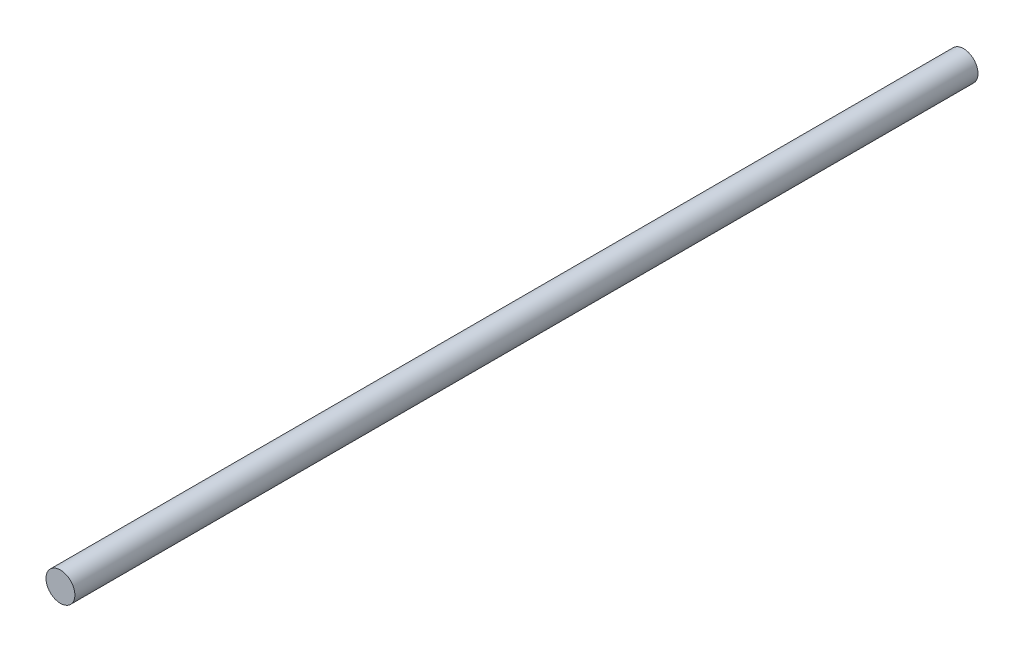
SolidWorks part; units mm, degrees
material "1.4000 (X6Cr13)"
ref_plane "Plan de face" through (0, 0, 0) normal (0, 0, 1) x (1, 0, 0)
ref_plane "Plan de dessus" through (0, 0, 0) normal (0, 1, 0) x (1, 0, 0)
ref_plane "Plan de droite" through (0, 0, 0) normal (1, 0, 0) x (0, 0, -1)
sketch "Esquisse1" plane through (0, 0, 0) normal (0, 0, 1) x (1, 0, 0)
  circle A0 centre (0, 0) radius 4
extrude "Boss.-Extru.1" add sketch "Esquisse1" along normal blind 250
ref_plane "SectionMiBarreY" through (0, 0, 125) normal (0, 0, -1) x (-1, 0, 0)
